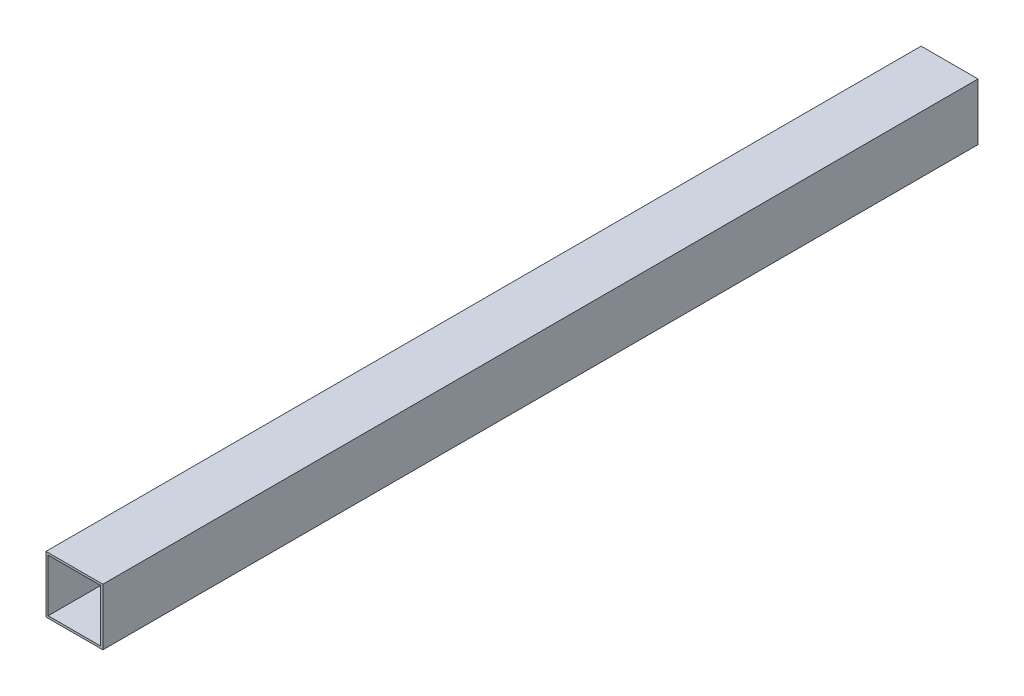
SolidWorks part; units mm, degrees
ref_plane "Front Plane" through (0, 0, 0) normal (0, 0, 1) x (1, 0, 0)
ref_plane "Top Plane" through (0, 0, 0) normal (0, 1, 0) x (1, 0, 0)
ref_plane "Right Plane" through (0, 0, 0) normal (1, 0, 0) x (0, 0, -1)
sketch "Sketch1" plane through (0, 0, 0) normal (0, 0, 1) x (1, 0, 0)
  line L1 (6, 6) -> (-6, 6)
  line L2 (6, 6) -> (6, -6)
  line L3 (6, -6) -> (-6, -6)
  line L4 (-6, 6) -> (-6, -6)
  line L5 (6, 6) -> (-6, -6) construction
  line L6 (6, -6) -> (-6, 6) construction
  line L7 (-6.5, 6.5) -> (6.5, 6.5)
  line L8 (-6.5, 6.5) -> (-6.5, -6.5)
  line L9 (-6.5, -6.5) -> (6.5, -6.5)
  line L10 (6.5, 6.5) -> (6.5, -6.5)
  line L11 (-6.5, 6.5) -> (6.5, -6.5) construction
  line L12 (-6.5, -6.5) -> (6.5, 6.5) construction
  point P1 (0, 0)
  point P6 (0, 0)
  dimension "D1" = 12
  dimension "D2" = 13
  dimension "D3" = 13
  dimension "D4" = 12
extrude "Boss-Extrude1" add sketch "Sketch1" along normal blind 200
